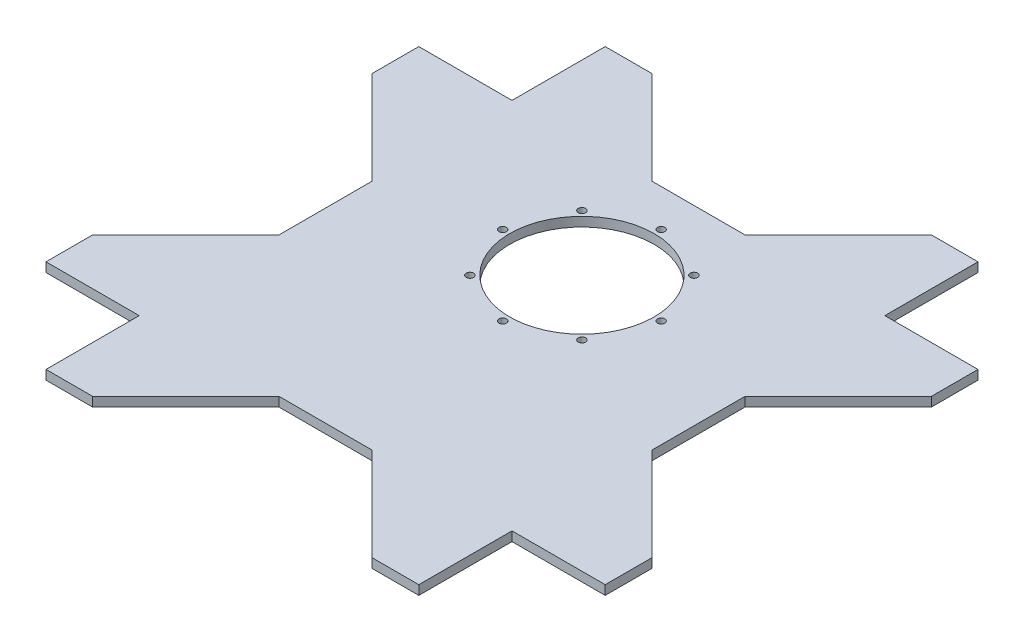
SolidWorks part; units mm, degrees
ref_plane "前视基准面" through (0, 0, 0) normal (0, 0, 1) x (1, 0, 0)
ref_plane "上视基准面" through (0, 0, 0) normal (0, 1, 0) x (1, 0, 0)
ref_plane "右视基准面" through (0, 0, 0) normal (1, 0, 0) x (0, 0, -1)
other "Configuration Table"
sketch "草图1" plane through (0, 0, 0) normal (0, 1, 0) x (1, 0, 0)
  line L1 (0, 0) -> (160, 0)
  line L2 (0, 0) -> (0, 160)
  line L3 (0, 160) -> (160, 160)
  line L4 (160, 0) -> (160, 160)
  dimension "D1" = 160
  dimension "D2" = 160
extrude "凸台-拉伸1" add sketch "草图1" along normal blind 4
sketch "草图2" plane through (0, 4, 0) normal (0, 1, 0) x (1, 0, 0)
  line L0 (0, 100) -> (-40, 140)
  line L1 (0, 160) -> (0, 0) construction
  line L2 (-40, 140) -> (-40, 160)
  line L3 (-40, 160) -> (0, 160)
  line L4 (0, 160) -> (0, 200)
  line L5 (0, 200) -> (20, 200)
  line L6 (20, 200) -> (60, 160)
  line L7 (160, 160) -> (0, 160) construction
  line L8 (60, 160) -> (0, 100)
  line L9 (-65.8007, 80) -> (246.0394, 80) construction
  line L10 (80, 215.1305) -> (80, -18.8063) construction
  line L11 (160, 0) -> (160, 160) construction
  line L12 (0, 0) -> (160, 0) construction
  line L13 (60, 0) -> (0, 60)
  line L14 (20, -40) -> (60, 0)
  line L15 (0, -40) -> (20, -40)
  line L16 (0, 0) -> (0, -40)
  line L17 (-40, 0) -> (0, 0)
  line L18 (-40, 20) -> (-40, 0)
  line L19 (0, 60) -> (-40, 20)
  line L20 (160, 60) -> (200, 20)
  line L21 (200, 20) -> (200, 0)
  line L22 (200, 0) -> (160, 0)
  line L23 (160, 0) -> (160, -40)
  line L24 (160, -40) -> (140, -40)
  line L25 (140, -40) -> (100, 0)
  line L26 (100, 0) -> (160, 60)
  line L27 (100, 160) -> (160, 100)
  line L28 (140, 200) -> (100, 160)
  line L29 (160, 200) -> (140, 200)
  line L30 (160, 160) -> (160, 200)
  line L31 (200, 160) -> (160, 160)
  line L32 (200, 140) -> (200, 160)
  line L33 (160, 100) -> (200, 140)
  dimension "D1" = 20
  dimension "D2" = 20
  dimension "D3" = 45
  dimension "D4" = 45
  dimension "D5" = 40
  dimension "D6" = 40
extrude "凸台-拉伸2" add sketch "草图2" against normal up to surface (4 mm away) up to face at (80, 0, -80)
sketch "草图3" plane through (0, 0, 0) normal (0, -1, 0) x (1, 0, 0)
  line L0 (80, -160) -> (80, 0) construction
  line L1 (100, -160) -> (60, -160) construction
  line L2 (60, 0) -> (100, 0) construction
  circle A0 centre (80, -110) radius 31
  circle A1 centre (80, -110) radius 34 construction
  circle A2 centre (80, -76) radius 1.6
  circle A3 centre (104.0416, -85.9584) radius 1.6
  circle A4 centre (114, -110) radius 1.6
  circle A5 centre (104.0416, -134.0416) radius 1.6
  circle A6 centre (80, -144) radius 1.6
  circle A7 centre (55.9584, -134.0416) radius 1.6
  circle A8 centre (46, -110) radius 1.6
  circle A9 centre (55.9584, -85.9584) radius 1.6
  dimension "D1" = 62
  dimension "D2" = 68
  dimension "D3" = 3.2
  dimension "D5" = 50
  dimension "D4" = 8
extrude "切除-拉伸2" cut sketch "草图3" against normal blind 10
